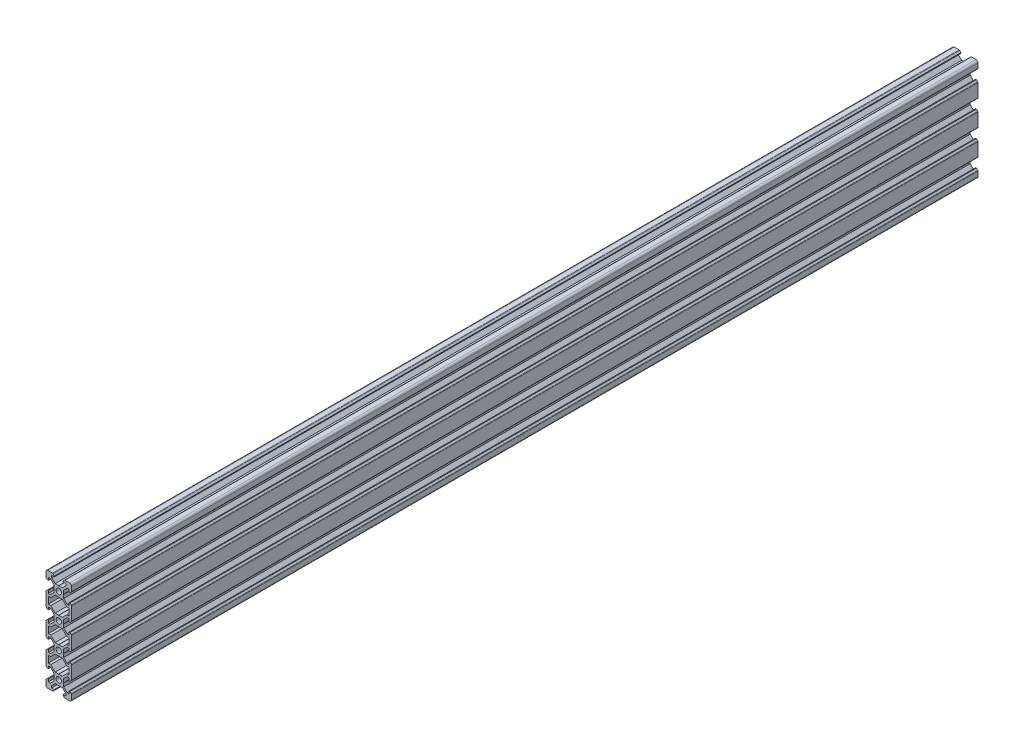
SolidWorks part; units mm, degrees
material "6063-T5"
ref_plane "Front" through (0, 0, 0) normal (0, 0, 1) x (1, 0, 0)
ref_plane "Top" through (0, 0, 0) normal (0, 1, 0) x (1, 0, 0)
ref_plane "Right" through (0, 0, 0) normal (1, 0, 0) x (0, 0, -1)
sketch "Sketch1" plane through (0, 0, 0) normal (0, 0, 1) x (1, 0, 0)
  line L0 (-8.5, 10) -> (-10, 8.5) construction
  line L1 (-8.5, 10) -> (-4.8628, 10)
  line L2 (-10, 8.5) -> (-10, 4.8628)
  line L3 (-2.8395, -23.9005) -> (-0.1, -23.9005)
  line L4 (10, 8.5) -> (10, 4.8628)
  line L5 (-10, 10) -> (10, -10) construction
  line L6 (-10, -10) -> (10, 10) construction
  line L7 (8.2, -5.5) -> (8.2, -3.3865)
  line L8 (-8.2, -5.5) -> (-8.2, -3.3865)
  line L9 (-5.5, 8.2) -> (-3.3865, 8.2)
  line L10 (-8.2, -12.7) -> (-8.2, -7.3)
  line L11 (-3.9005, 2.8395) -> (-6.561, 5.5)
  line L12 (-6.561, 5.5) -> (-8.2, 5.5)
  line L13 (-2.8395, -3.9005) -> (-0.1, -3.9005)
  line L14 (-3.9005, -2.8395) -> (-3.9005, -0.1)
  line L15 (-2.8395, 3.9005) -> (-0.1, 3.9005)
  line L16 (3.9005, -2.8395) -> (3.9005, -0.1)
  line L17 (-8.2, 3.3865) -> (-8.81, 3.3865)
  line L18 (-8.81, 3.3865) -> (-9.7976, 4.3741)
  line L19 (8.5, 10) -> (10, 8.5) construction
  line L20 (-2.8395, 3.9005) -> (-5.5, 6.561)
  line L21 (-5.5, 6.561) -> (-5.5, 8.2)
  line L22 (-3.3865, 8.2) -> (-3.3865, 8.81)
  line L23 (-3.3865, 8.81) -> (-4.3741, 9.7976)
  line L24 (0, 24.069) -> (0, -84.2588) construction
  line L25 (3.3865, 8.81) -> (4.3741, 9.7976)
  line L26 (3.3865, 8.2) -> (3.3865, 8.81)
  line L27 (5.5, 6.561) -> (5.5, 8.2)
  line L28 (2.8395, 3.9005) -> (5.5, 6.561)
  line L29 (3.3865, 8.2) -> (5.5, 8.2)
  line L30 (4.8628, 10) -> (8.5, 10)
  line L31 (-0.1, 3.9005) -> (0, 3.8005)
  line L32 (0.1, 3.9005) -> (0, 3.8005)
  line L33 (0.1, 3.9005) -> (2.8395, 3.9005)
  line L34 (25.9287, 0) -> (-28.3459, 0) construction
  line L35 (-0.1, -3.9005) -> (0, -3.8005)
  line L36 (0.1, -3.9005) -> (0, -3.8005)
  line L37 (0.1, -3.9005) -> (2.8395, -3.9005)
  line L38 (-3.9005, 0.1) -> (-3.8005, 0)
  line L39 (-3.8005, 0) -> (-3.9005, -0.1)
  line L40 (-3.9005, 0.1) -> (-3.9005, 2.8395)
  line L41 (3.9005, 0.1) -> (3.8005, 0)
  line L42 (3.8005, 0) -> (3.9005, -0.1)
  line L43 (3.9005, 0.1) -> (3.9005, 2.8395)
  line L44 (8.81, 3.3865) -> (9.7976, 4.3741)
  line L45 (8.2, 3.3865) -> (8.81, 3.3865)
  line L46 (6.561, 5.5) -> (8.2, 5.5)
  line L47 (3.9005, 2.8395) -> (6.561, 5.5)
  line L48 (2.8395, -3.9005) -> (5.5, -6.561)
  line L49 (3.9005, -2.8395) -> (6.561, -5.5)
  line L50 (-2.8395, -3.9005) -> (-5.5, -6.561)
  line L51 (-3.9005, -2.8395) -> (-6.561, -5.5)
  line L52 (6.561, -5.5) -> (8.2, -5.5)
  line L53 (-6.561, -5.5) -> (-8.2, -5.5)
  line L54 (-8.81, -3.3865) -> (-9.7976, -4.3741)
  line L55 (-8.2, -3.3865) -> (-8.81, -3.3865)
  line L56 (8.81, -3.3865) -> (9.7976, -4.3741)
  line L57 (8.2, -3.3865) -> (8.81, -3.3865)
  line L58 (8.2, 3.3865) -> (8.2, 5.5)
  line L59 (10, -4.8628) -> (10, -15.1372)
  line L60 (-8.2, 3.3865) -> (-8.2, 5.5)
  line L61 (25.9287, -10) -> (-24.6023, -10) construction
  line L62 (8.2, -12.7) -> (8.2, -7.3)
  line L63 (0.1, -23.9005) -> (2.8395, -23.9005)
  line L64 (-0.1, -23.9005) -> (0, -23.8005)
  line L65 (-3.9005, -22.8395) -> (-3.9005, -20.1)
  line L66 (0.1, -23.9005) -> (0, -23.8005)
  line L67 (-2.8395, -43.9005) -> (-0.1, -43.9005)
  line L68 (-3.8005, -20) -> (-3.9005, -20.1)
  line L69 (2.8395, -16.0995) -> (5.5, -13.439)
  line L70 (3.9005, -17.1605) -> (6.561, -14.5)
  line L71 (-3.9005, -19.9) -> (-3.8005, -20)
  line L72 (-3.9005, -19.9) -> (-3.9005, -17.1605)
  line L73 (3.9005, -22.8395) -> (6.561, -25.5)
  line L74 (5.5, -13.439) -> (6.239, -12.7)
  line L75 (-8.2, -14.5) -> (-8.2, -16.6135)
  line L76 (-8.2, -16.6135) -> (-8.81, -16.6135)
  line L77 (-8.81, -16.6135) -> (-9.7976, -15.6259)
  line L78 (8.81, -16.6135) -> (9.7976, -15.6259)
  line L79 (2.8395, -23.9005) -> (5.5, -26.561)
  line L80 (-2.8395, -16.0995) -> (-0.1, -16.0995)
  line L81 (0.1, -16.0995) -> (2.8395, -16.0995)
  line L82 (0.1, -16.0995) -> (0, -16.1995)
  line L83 (-0.1, -16.0995) -> (0, -16.1995)
  line L84 (-2.8395, -23.9005) -> (-5.5, -26.561)
  line L85 (8.2, -16.6135) -> (8.81, -16.6135)
  line L86 (8.2, -14.5) -> (8.2, -16.6135)
  line L87 (0.1, -43.9005) -> (2.8395, -43.9005)
  line L88 (-0.1, -43.9005) -> (0, -43.8005)
  line L89 (0.1, -43.9005) -> (0, -43.8005)
  line L90 (-2.8395, -63.9005) -> (-0.1, -63.9005)
  line L91 (0.1, -63.9005) -> (2.8395, -63.9005)
  line L92 (-0.1, -63.9005) -> (0, -63.8005)
  line L93 (0.1, -63.9005) -> (0, -63.8005)
  line L94 (-2.8395, -36.0995) -> (-0.1, -36.0995)
  line L95 (0.1, -36.0995) -> (2.8395, -36.0995)
  line L96 (0.1, -36.0995) -> (0, -36.1995)
  line L97 (-0.1, -36.0995) -> (0, -36.1995)
  line L98 (-2.8395, -56.0995) -> (-0.1, -56.0995)
  line L99 (0.1, -56.0995) -> (2.8395, -56.0995)
  line L100 (0.1, -56.0995) -> (0, -56.1995)
  line L101 (-0.1, -56.0995) -> (0, -56.1995)
  line L102 (3.9005, -22.8395) -> (3.9005, -20.1)
  line L103 (3.8005, -20) -> (3.9005, -20.1)
  line L104 (3.9005, -19.9) -> (3.8005, -20)
  line L105 (3.9005, -19.9) -> (3.9005, -17.1605)
  line L106 (-3.9005, -42.8395) -> (-3.9005, -40.1)
  line L107 (-3.8005, -40) -> (-3.9005, -40.1)
  line L108 (-3.9005, -39.9) -> (-3.8005, -40)
  line L109 (-3.9005, -39.9) -> (-3.9005, -37.1605)
  line L110 (3.9005, -42.8395) -> (3.9005, -40.1)
  line L111 (3.8005, -40) -> (3.9005, -40.1)
  line L112 (3.9005, -39.9) -> (3.8005, -40)
  line L113 (3.9005, -39.9) -> (3.9005, -37.1605)
  line L114 (-3.9005, -62.8395) -> (-3.9005, -60.1)
  line L115 (-6.239, -7.3) -> (-8.2, -7.3)
  line L116 (-5.5, -6.561) -> (-6.239, -7.3)
  line L117 (6.239, -7.3) -> (8.2, -7.3)
  line L118 (5.5, -6.561) -> (6.239, -7.3)
  line L119 (-6.239, -12.7) -> (-8.2, -12.7)
  line L120 (-2.8395, -16.0995) -> (-5.5, -13.439)
  line L121 (2.8395, -36.0995) -> (5.5, -33.439)
  line L122 (6.239, -12.7) -> (8.2, -12.7)
  line L123 (-10, -15.1372) -> (-10, -4.8628)
  line L124 (-3.8005, -60) -> (-3.9005, -60.1)
  line L125 (10, -24.8628) -> (10, -35.1372)
  line L126 (-3.9005, -59.9) -> (-3.8005, -60)
  line L127 (8.2, -30) -> (-28.3599, -30) construction
  line L128 (-3.9005, -59.9) -> (-3.9005, -57.1605)
  line L129 (3.9005, -62.8395) -> (3.9005, -60.1)
  line L130 (3.8005, -60) -> (3.9005, -60.1)
  line L131 (3.9005, -59.9) -> (3.8005, -60)
  line L132 (3.9005, -59.9) -> (3.9005, -57.1605)
  line L133 (-3.9005, -22.8395) -> (-6.561, -25.5)
  line L134 (-3.9005, -17.1605) -> (-6.561, -14.5)
  line L135 (3.9005, -37.1605) -> (6.561, -34.5)
  line L136 (3.9005, -42.8395) -> (6.561, -45.5)
  line L137 (-3.9005, -42.8395) -> (-6.561, -45.5)
  line L138 (-3.9005, -37.1605) -> (-6.561, -34.5)
  line L139 (3.9005, -57.1605) -> (6.561, -54.5)
  line L140 (3.9005, -62.8395) -> (6.561, -65.5)
  line L141 (-3.9005, -62.8395) -> (-6.561, -65.5)
  line L142 (-3.9005, -57.1605) -> (-6.561, -54.5)
  line L143 (2.8395, -43.9005) -> (5.5, -46.561)
  line L144 (-2.8395, -43.9005) -> (-5.5, -46.561)
  line L145 (-2.8395, -36.0995) -> (-5.5, -33.439)
  line L146 (2.8395, -56.0995) -> (5.5, -53.439)
  line L147 (2.8395, -63.9005) -> (5.5, -66.561)
  line L148 (-2.8395, -63.9005) -> (-5.5, -66.561)
  line L149 (-2.8395, -56.0995) -> (-5.5, -53.439)
  line L150 (-5.5, -13.439) -> (-6.239, -12.7)
  line L151 (6.561, -14.5) -> (8.2, -14.5)
  line L152 (-6.561, -14.5) -> (-8.2, -14.5)
  line L153 (10, -44.8628) -> (10, -55.1372)
  line L154 (-10, -35.1372) -> (-10, -24.8628)
  line L155 (8.2, -23.3865) -> (8.81, -23.3865)
  line L156 (8.81, -23.3865) -> (9.7976, -24.3741)
  line L157 (8.2, -25.5) -> (8.2, -23.3865)
  line L158 (8.2, -34.5) -> (8.2, -36.6135)
  line L159 (8.2, -36.6135) -> (8.81, -36.6135)
  line L160 (8.81, -36.6135) -> (9.7976, -35.6259)
  line L161 (-8.81, -36.6135) -> (-9.7976, -35.6259)
  line L162 (-8.2, -36.6135) -> (-8.81, -36.6135)
  line L163 (-8.2, -34.5) -> (-8.2, -36.6135)
  line L164 (-8.81, -23.3865) -> (-9.7976, -24.3741)
  line L165 (-8.2, -23.3865) -> (-8.81, -23.3865)
  line L166 (-8.2, -25.5) -> (-8.2, -23.3865)
  line L167 (-10, -55.1372) -> (-10, -44.8628)
  line L168 (8.2, -43.3865) -> (8.81, -43.3865)
  line L169 (8.81, -43.3865) -> (9.7976, -44.3741)
  line L170 (8.2, -45.5) -> (8.2, -43.3865)
  line L171 (8.2, -54.5) -> (8.2, -56.6135)
  line L172 (8.2, -56.6135) -> (8.81, -56.6135)
  line L173 (8.81, -56.6135) -> (9.7976, -55.6259)
  line L174 (-8.81, -56.6135) -> (-9.7976, -55.6259)
  line L175 (-8.2, -56.6135) -> (-8.81, -56.6135)
  line L176 (-8.2, -54.5) -> (-8.2, -56.6135)
  line L177 (-8.81, -43.3865) -> (-9.7976, -44.3741)
  line L178 (-8.2, -43.3865) -> (-8.81, -43.3865)
  line L179 (-8.2, -45.5) -> (-8.2, -43.3865)
  line L180 (-8.2, -32.7) -> (-8.2, -27.3)
  line L181 (8.2, -32.7) -> (8.2, -27.3)
  line L182 (6.239, -27.3) -> (8.2, -27.3)
  line L183 (6.239, -32.7) -> (8.2, -32.7)
  line L184 (-6.239, -32.7) -> (-8.2, -32.7)
  line L185 (-6.239, -27.3) -> (-8.2, -27.3)
  line L186 (-8.2, -52.7) -> (-8.2, -47.3)
  line L187 (8.2, -52.7) -> (8.2, -47.3)
  line L188 (6.239, -47.3) -> (8.2, -47.3)
  line L189 (6.239, -52.7) -> (8.2, -52.7)
  line L190 (-6.239, -52.7) -> (-8.2, -52.7)
  line L191 (-6.239, -47.3) -> (-8.2, -47.3)
  line L192 (5.5, -33.439) -> (6.239, -32.7)
  line L193 (-5.5, -33.439) -> (-6.239, -32.7)
  line L194 (6.561, -34.5) -> (8.2, -34.5)
  line L195 (-6.561, -34.5) -> (-8.2, -34.5)
  line L196 (6.561, -25.5) -> (8.2, -25.5)
  line L197 (5.5, -26.561) -> (6.239, -27.3)
  line L198 (-5.5, -26.561) -> (-6.239, -27.3)
  line L199 (-6.561, -25.5) -> (-8.2, -25.5)
  line L200 (5.5, -53.439) -> (6.239, -52.7)
  line L201 (-5.5, -53.439) -> (-6.239, -52.7)
  line L202 (6.561, -54.5) -> (8.2, -54.5)
  line L203 (-6.561, -54.5) -> (-8.2, -54.5)
  line L204 (6.561, -45.5) -> (8.2, -45.5)
  line L205 (5.5, -46.561) -> (6.239, -47.3)
  line L206 (-5.5, -46.561) -> (-6.239, -47.3)
  line L207 (-6.561, -45.5) -> (-8.2, -45.5)
  line L208 (-5.5, -66.561) -> (-5.5, -68.2)
  line L209 (5.5, -66.561) -> (5.5, -68.2)
  line L210 (3.3865, -68.2) -> (3.3865, -68.81)
  line L211 (3.3865, -68.2) -> (5.5, -68.2)
  line L212 (-5.5, -68.2) -> (-3.3865, -68.2)
  line L213 (-3.3865, -68.2) -> (-3.3865, -68.81)
  line L214 (-3.3865, -68.81) -> (-4.3741, -69.7976)
  line L215 (3.3865, -68.81) -> (4.3741, -69.7976)
  line L216 (-8.5, -70) -> (-4.8628, -70)
  line L217 (4.8628, -70) -> (8.5, -70)
  line L218 (6.561, -65.5) -> (8.2, -65.5)
  line L219 (-8.2, -63.3865) -> (-8.2, -65.5)
  line L220 (-6.561, -65.5) -> (-8.2, -65.5)
  line L221 (8.2, -63.3865) -> (8.2, -65.5)
  line L222 (8.2, -63.3865) -> (8.81, -63.3865)
  line L223 (-8.2, -63.3865) -> (-8.81, -63.3865)
  line L224 (-8.81, -63.3865) -> (-9.7976, -64.3741)
  line L225 (8.81, -63.3865) -> (9.7976, -64.3741)
  line L226 (-10, -68.5) -> (-10, -64.8628)
  line L227 (10, -68.5) -> (10, -64.8628)
  circle A0 centre (0, 0) radius 2.1
  arc A1 (-8.5, 10) -> (-10, 8.5) centre (-8.5, 8.5) ccw
  arc A2 (10, 8.5) -> (8.5, 10) centre (8.5, 8.5) ccw
  arc A3 (-4.3741, 9.7976) -> (-4.8628, 10) centre (-4.8628, 9.3088) ccw
  arc A4 (4.8628, 10) -> (4.3741, 9.7976) centre (4.8628, 9.3088) ccw
  circle A5 centre (0, -20) radius 2.1
  arc A6 (9.7976, 4.3741) -> (10, 4.8628) centre (9.3088, 4.8628) ccw
  arc A7 (-10, 4.8628) -> (-9.7976, 4.3741) centre (-9.3088, 4.8628) ccw
  arc A8 (-10, -4.8628) -> (-9.7976, -4.3741) centre (-9.3088, -4.8628) cw
  arc A9 (9.7976, -4.3741) -> (10, -4.8628) centre (9.3088, -4.8628) cw
  arc A10 (-10, -15.1372) -> (-9.7976, -15.6259) centre (-9.3088, -15.1372) ccw
  arc A11 (9.7976, -15.6259) -> (10, -15.1372) centre (9.3088, -15.1372) ccw
  circle A12 centre (0, -40) radius 2.1
  circle A13 centre (0, -60) radius 2.1
  arc A14 (9.7976, -24.3741) -> (10, -24.8628) centre (9.3088, -24.8628) cw
  arc A15 (9.7976, -35.6259) -> (10, -35.1372) centre (9.3088, -35.1372) ccw
  arc A16 (-10, -35.1372) -> (-9.7976, -35.6259) centre (-9.3088, -35.1372) ccw
  arc A17 (-10, -24.8628) -> (-9.7976, -24.3741) centre (-9.3088, -24.8628) cw
  arc A18 (9.7976, -44.3741) -> (10, -44.8628) centre (9.3088, -44.8628) cw
  arc A19 (9.7976, -55.6259) -> (10, -55.1372) centre (9.3088, -55.1372) ccw
  arc A20 (-10, -55.1372) -> (-9.7976, -55.6259) centre (-9.3088, -55.1372) ccw
  arc A21 (-10, -44.8628) -> (-9.7976, -44.3741) centre (-9.3088, -44.8628) cw
  arc A22 (10, -68.5) -> (8.5, -70) centre (8.5, -68.5) cw
  arc A23 (-8.5, -70) -> (-10, -68.5) centre (-8.5, -68.5) cw
  arc A24 (4.8628, -70) -> (4.3741, -69.7976) centre (4.8628, -69.3088) cw
  arc A25 (-4.3741, -69.7976) -> (-4.8628, -70) centre (-4.8628, -69.3088) cw
  arc A26 (9.7976, -64.3741) -> (10, -64.8628) centre (9.3088, -64.8628) cw
  arc A27 (-10, -64.8628) -> (-9.7976, -64.3741) centre (-9.3088, -64.8628) cw
  point P17 (-9.25, 9.25)
  point P21 (9.25, 9.25)
  dimension "D2" = 4.2
  dimension "D4" = 1.5
  dimension "D3" = 20
  dimension "D5" = 0.529
  dimension "D6" = 6.773
  dimension "D7" = 90
  dimension "D8" = 11
  dimension "D9" = 0.61
  dimension "D10" = 0.1
  dimension "D11" = 0.1
  dimension "D12" = 0.1
  dimension "D13" = 0.1
  dimension "D14" = 5.679
  dimension "D15" = 1.639
  dimension "D16" = 1.8
  dimension "D17" = 90
  dimension "D18" = 6.773
  dimension "D19" = 90
  dimension "D20" = 4
  dimension "D21" = 1.8
  dimension "D22" = 3
extrude "Boss-Extrude2" add sketch "Sketch1" along normal blind 710
